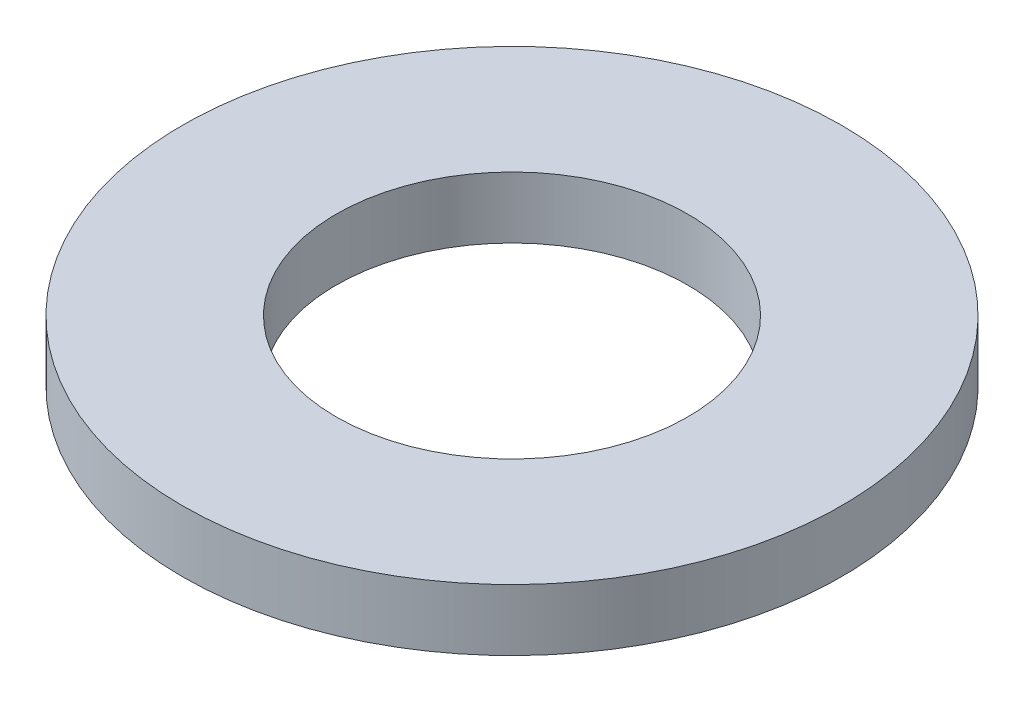
SolidWorks part; units mm, degrees
ref_plane "Front Plane" through (0, 0, 0) normal (0, 0, 1) x (1, 0, 0)
ref_plane "Top Plane" through (0, 0, 0) normal (0, 1, 0) x (1, 0, 0)
ref_plane "Right Plane" through (0, 0, 0) normal (1, 0, 0) x (0, 0, -1)
sketch "Sketch1" plane through (0, 0, 0) normal (0, 1, 0) x (1, 0, 0)
  circle A0 centre (0, 0) radius 4
  circle A1 centre (0, 0) radius 7.5
  dimension "D1" = 8
  dimension "D2" = 15
extrude "Boss-Extrude1" add sketch "Sketch1" along normal blind 1.4
